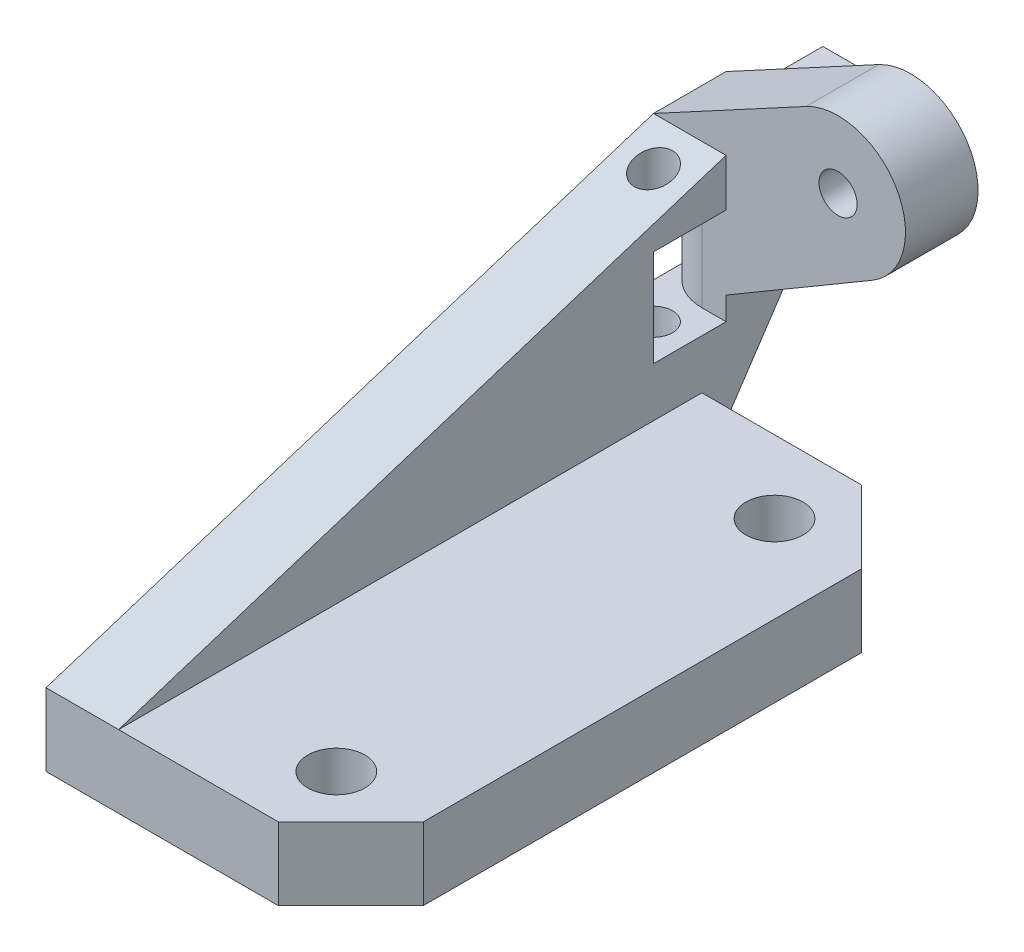
SolidWorks part; units mm, degrees
ref_plane "Front Plane" through (0, 0, 0) normal (0, 0, 1) x (1, 0, 0)
ref_plane "Top Plane" through (0, 0, 0) normal (0, 1, 0) x (1, 0, 0)
ref_plane "Right Plane" through (0, 0, 0) normal (1, 0, 0) x (0, 0, -1)
sketch "Sketch1" plane through (0, 0, 0) normal (0, 1, 0) x (1, 0, 0)
  line L0 (7.62, 30.62) -> (7.62, 26.81) construction
  line L1 (0, 0) -> (12.192, 0)
  line L2 (0, 0) -> (0, 30.62)
  line L3 (0, 30.62) -> (12.192, 30.62)
  line L4 (12.192, 0) -> (12.192, 30.62)
  line L5 (7.62, 26.81) -> (7.62, 3.81) construction
  line L6 (7.62, 3.81) -> (7.62, 0) construction
  circle A0 centre (7.62, 26.81) radius 1.5
  circle A1 centre (7.62, 3.81) radius 1.5
  point P10 (5.8003, 29.2092)
  point P12 (0, 0)
  point P13 (0, 0)
  dimension "D1" = 3
  dimension "D2" = 23
  dimension "D3" = 4.572
  dimension "D4" = 3.81
  dimension "D5" = 7.62
extrude "Boss-Extrude1" add sketch "Sketch1" along normal blind 3.81
sketch "Sketch2" plane through (0, 0, 0) normal (-1, 0, 0) x (0, 0, 1)
  line L0 (0, 3.81) -> (0, 0) construction
  line L1 (-30.62, 0) -> (0, 0) construction
  line L2 (0, 3.81) -> (0, 0)
  line L3 (-30.62, 0) -> (0, 0)
  line L4 (-30.62, 0) -> (-35.7, 7.62)
  line L5 (-35.7, 7.62) -> (-35.7, 13.97)
  line L7 (-30.62, 3.81) -> (-30.62, 0) construction
  line L8 (-35.7, 13.97) -> (-31.89, 13.97)
  line L9 (-31.89, 13.97) -> (0, 3.81)
  dimension "D1" = 5.08
  dimension "D2" = 7.62
  dimension "D3" = 6.35
  dimension "D4" = 3.81
extrude "Boss-Extrude2" add sketch "Sketch2" along normal blind 3.81
sketch "Sketch3" plane through (0, 0, -35.7) normal (0, 0, -1) x (-1, 0, 0)
  line L0 (3.81, 13.97) -> (3.81, 7.62) construction
  line L1 (3.81, 7.62) -> (2.032, 7.62)
  line L2 (3.81, 7.62) -> (3.81, 9.398)
  line L3 (3.81, 9.398) -> (2.032, 9.398)
  line L4 (2.032, 7.62) -> (2.032, 9.398)
  line L5 (3.81, 10.795) -> (2.032, 10.795)
  line L6 (3.81, 10.795) -> (3.81, 12.573)
  line L7 (3.81, 12.573) -> (2.032, 12.573)
  line L8 (2.032, 10.795) -> (2.032, 12.573)
  dimension "D1" = 1.778
  dimension "D2" = 1.778
extrude "Boss-Extrude3" add sketch "Sketch3" along normal blind 5.08
sketch "Sketch4" plane through (0, 0, -35.7) normal (0, 0, -1) x (-1, 0, 0)
  line L0 (0, 7.62) -> (-7.6703, 12.1238)
  line L1 (-4.1963, 18.2917) -> (3.81, 13.97)
  line L2 (3.81, 13.97) -> (0, 13.97)
  line L3 (0, 13.97) -> (0, 7.62)
  line L4 (-995.809, 10.0965) -> (49004.191, 10.0965) construction
  line L5 (2.032, 9.398) -> (3.81, 9.398) construction
  line L6 (2.032, 9.398) -> (2.032, 10.795) construction
  line L7 (2.032, 10.795) -> (3.81, 10.795) construction
  line L8 (3.81, 9.398) -> (3.81, 10.795) construction
  line L9 (2.032, 9.398) -> (3.81, 10.795) construction
  line L10 (2.032, 10.795) -> (3.81, 9.398) construction
  line L11 (-5.8778, 15.1765) -> (2.921, 10.0965) construction
  circle A0 centre (-5.8778, 15.1765) radius 1
  arc A1 (-7.6703, 12.1238) -> (-4.1963, 18.2917) centre (-5.8778, 15.1765) cw
  point P12 (2.921, 10.0965)
  dimension "D2" = 2.54
  dimension "D3" = 2
  dimension "D1" = 30
  dimension "D4" = 10.16
extrude "Boss-Extrude4" add sketch "Sketch4" against normal up to vertex (3.81 mm away) up to point (0, 13.97, -31.89)
sketch "Sketch5" plane through (-3.81, 0, 0) normal (-1, 0, 0) x (0, 0, 1)
  line L0 (0, 3.81) -> (-31.89, 13.97) construction
  line L1 (-31.89, 11.4862) -> (-28.08, 11.4862)
  line L2 (-31.89, 11.4862) -> (-31.89, 6.4062)
  line L3 (-31.89, 6.4062) -> (-28.08, 6.4062)
  line L4 (-28.08, 11.4862) -> (-28.08, 6.4062)
  line L5 (-28.08, 11.4862) -> (-28.08, 12.7562) construction
  line L7 (-31.89, 13.97) -> (-31.89, 18.2917) construction
  dimension "D1" = 3.81
  dimension "D2" = 5.08
  dimension "D3" = 1.27
extrude "Cut-Extrude1" cut sketch "Sketch5" against normal up to next
sketch "Sketch6" plane through (0, 6.4062, 0) normal (0, 1, 0) x (1, 0, 0)
  line L1 (0, 31.89) -> (-3.81, 31.89) construction
  line L2 (0, 31.89) -> (0, 28.08) construction
  line L3 (0, 28.08) -> (-3.81, 28.08) construction
  line L4 (-3.81, 31.89) -> (-3.81, 28.08) construction
  line L5 (0, 31.89) -> (-3.81, 28.08) construction
  line L6 (0, 28.08) -> (-3.81, 31.89) construction
  circle A0 centre (-1.905, 29.985) radius 1
  point P0 (-1.905, 29.985)
  dimension "D1" = 2
extrude "Cut-Extrude2" cut sketch "Sketch6" along normal through all and the other way blind 5.08 draft 5
chamfer "Chamfer1" distance 0.762 angle 45 3 edges at (-2.032, 10.795, -38.24) (-2.032, 9.398, -38.24) (-3.81, 9.398, -38.24)
fillet "Fillet1" radius 2.54 1 edges at (-3.81, 8.9462, -31.89)
chamfer "Chamfer2" distance 3.81 angle 45 2 edges at (12.192, 1.905, -30.62) (12.192, 1.905, 0)
fillet "Fillet2" radius 0.762 1 edges at (-3.81, 9.7155, -35.7)
